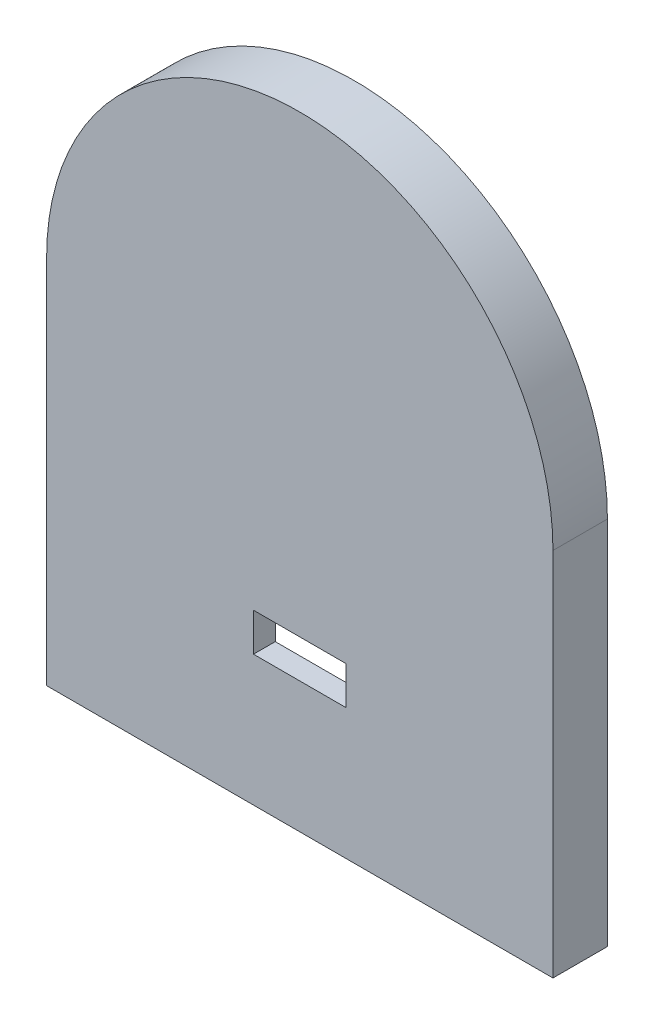
SolidWorks part; units mm, degrees
ref_plane "Front Plane" through (0, 0, 0) normal (0, 0, 1) x (1, 0, 0)
ref_plane "Top Plane" through (0, 0, 0) normal (0, 1, 0) x (1, 0, 0)
ref_plane "Right Plane" through (0, 0, 0) normal (1, 0, 0) x (0, 0, -1)
sketch "Sketch1" plane through (0, 0, 0) normal (0, 0, 1) x (1, 0, 0)
  line L0 (0, 0) -> (46.5, 0)
  line L1 (46.5, 0) -> (46.5, 34)
  line L2 (0, 0) -> (0, 34)
  line L3 (23.25, 0) -> (23.25, 57.25) construction
  line L4 (2, 2) -> (2, 34)
  line L5 (44.5, 2) -> (44.5, 34)
  line L6 (2, 2) -> (44.5, 2)
  arc A0 (0, 34) -> (46.5, 34) centre (23.25, 34) cw
  arc A1 (2, 34) -> (44.5, 34) centre (23.25, 34) cw
  point P16 (147.8212, 93.4511)
  point P17 (149.2541, 78.1165)
  dimension "D2" = 53.25
  dimension "D3" = 42.5
  dimension "D1" = 2
extrude "Boss-Extrude1" add sketch "Sketch1" along normal blind 3
sketch "Sketch2" plane through (0, 0, 3) normal (0, 0, 1) x (1, 0, 0)
  line L0 (0, 34) -> (0, 0)
  line L1 (0, 0) -> (46.5, 0)
  line L2 (46.5, 0) -> (46.5, 34)
  arc A0 (46.5, 34) -> (0, 34) centre (23.25, 34) ccw
extrude "Boss-Extrude2" add sketch "Sketch2" along normal blind 2
ref_plane "Plane1" through (0, 11.2, 0) normal (0, 1, 0) x (1, 0, 0)
sketch "Sketch3" plane through (0, 11.2, 0) normal (0, 1, 0) x (1, 0, 0)
  line L0 (2, 0) -> (2, -2)
  line L1 (2, -2) -> (3.7321, -1)
  line L2 (3.7321, -1) -> (2, 0)
  line L7 (46.5, 0) -> (0, 0)
  line L8 (0, 0) -> (0, -5)
  line L9 (0, -5) -> (46.5, -5)
  line L10 (46.5, -5) -> (46.5, 0)
  line L11 (46.5, 0) -> (0, 0)
  line L12 (0, 0) -> (0, -5)
  line L13 (0, -5) -> (46.5, -5)
  line L14 (46.5, -5) -> (46.5, 0)
  dimension "D1" = 2
  dimension "D2" = 60
  dimension "D3" = 0
  dimension "D4" = 0
  dimension "D5" = 2
  dimension "D6" = 60
extrude "Boss-Extrude3" add sketch "Sketch3" along normal blind 17.5 contours L1 L2 L0
ref_plane "Plane2" through (23.25, 0, 0) normal (-1, 0, 0) x (0, 0, 1)
mirror "Mirror1" about plane through (23.25, 0, 0) normal (-1, 0, 0) of "Boss-Extrude3"
sketch "Sketch4" plane through (0, 0, 3) normal (0, 0, -1) x (-1, 0, 0)
  line L1 (-27.5, 12) -> (-19, 12)
  line L2 (-27.5, 12) -> (-27.5, 15.5)
  line L3 (-27.5, 15.5) -> (-19, 15.5)
  line L4 (-19, 12) -> (-19, 15.5)
  line L5 (-27.5, 12) -> (-19, 15.5) construction
  line L6 (-27.5, 15.5) -> (-19, 12) construction
  line L7 (-23.25, -1.65) -> (-23.25, 1.65) construction
  line L8 (-2, 2) -> (-44.5, 2) construction
  point P0 (-23.25, 13.75)
  point P11 (-83.2621, 38.0021)
  point P12 (-70.5041, 24.2373)
  dimension "D1" = 8.5
  dimension "D2" = 3.5
  dimension "D3" = 10
extrude "Cut-Extrude1" cut sketch "Sketch4" against normal through all
